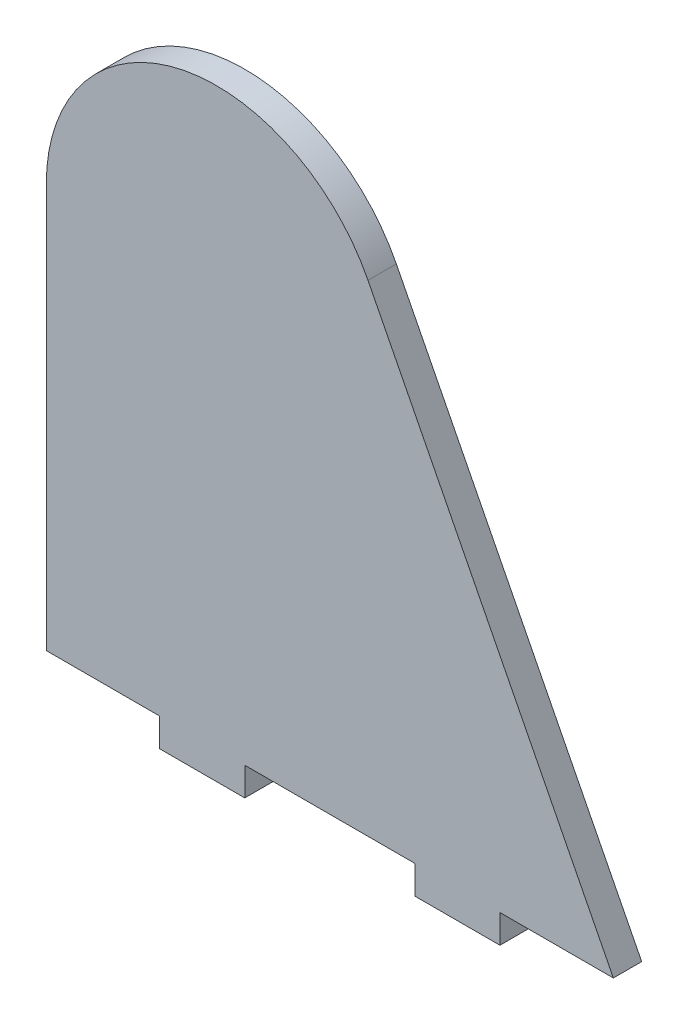
SolidWorks part; units mm, degrees
ref_plane "Front Plane" through (0, 0, 0) normal (0, 0, 1) x (1, 0, 0)
ref_plane "Top Plane" through (0, 0, 0) normal (0, 1, 0) x (1, 0, 0)
ref_plane "Right Plane" through (0, 0, 0) normal (1, 0, 0) x (0, 0, -1)
sketch "Sketch1" plane through (0, 0, 0) normal (0, 0, 1) x (1, 0, 0)
  line L0 (0, 71.3021) -> (0, 0)
  line L1 (0, 0) -> (20, 0)
  line L2 (100, 0) -> (56.7302, 84.9218)
  line L3 (80, 0) -> (100, 0)
  line L5 (20, 0) -> (20, -5)
  line L6 (20, -5) -> (35, -5)
  line L7 (35, 0) -> (35, -5)
  line L8 (35, 0) -> (65, 0)
  line L9 (65, 0) -> (65, -5)
  line L10 (65, -5) -> (80, -5)
  line L11 (80, 0) -> (80, -5)
  arc A0 (0, 71.3021) -> (56.7302, 84.9218) centre (30, 71.3021) cw
  dimension "D7" = 30
  dimension "D1" = 63
  dimension "D2" = 100
  dimension "D3" = 15
  dimension "D4" = 5
  dimension "D5" = 20
  dimension "D6" = 30
extrude "Boss-Extrude1" add sketch "Sketch1" along normal blind 5
